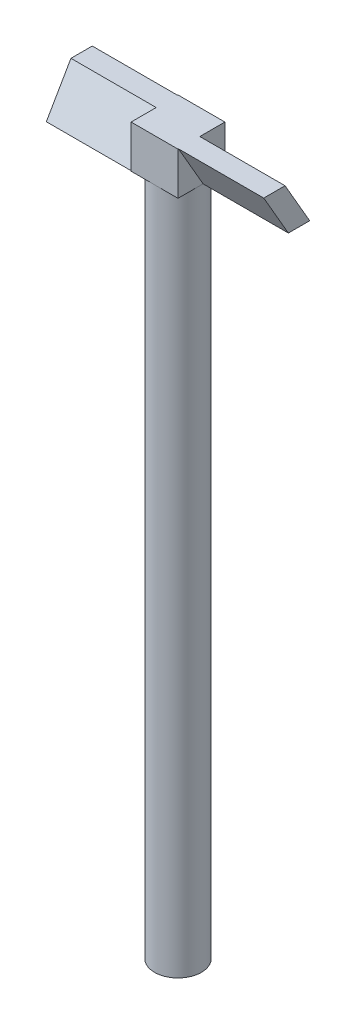
SolidWorks part; units mm, degrees
ref_plane "Front Plane" through (0, 0, 0) normal (0, 0, 1) x (1, 0, 0)
ref_plane "Top Plane" through (0, 0, 0) normal (0, 1, 0) x (1, 0, 0)
ref_plane "Right Plane" through (0, 0, 0) normal (1, 0, 0) x (0, 0, -1)
sketch "Sketch1" plane through (0, 0, 0) normal (0, 1, 0) x (1, 0, 0)
  circle A0 centre (0, 0) radius 5.5
  dimension "D1" = 11
extrude "Boss-Extrude1" add sketch "Sketch1" along normal blind 160 contours A0
sketch "Sketch2" plane through (0, 160, 0) normal (0, 1, 0) x (1, 0, 0)
  line L1 (-5.5, 5.5) -> (5.5, 5.5)
  line L2 (-5.5, 5.5) -> (-5.5, -5.5)
  line L3 (-5.5, -5.5) -> (5.5, -5.5)
  line L4 (5.5, 5.5) -> (5.5, -5.5)
  line L5 (-5.5, 5.5) -> (5.5, -5.5) construction
  line L6 (-5.5, -5.5) -> (5.5, 5.5) construction
  circle A0 centre (0, 0) radius 5.5 construction
  point P0 (0, 0)
  point P5 (0, -5.5)
  point P6 (0, 0)
extrude "Boss-Extrude2" add sketch "Sketch2" along normal blind 10
sketch "Sketch3" plane through (-5.5, 0, 0) normal (-1, 0, 0) x (0, 0, 1)
  line L0 (-5.3868, 170) -> (-0.3868, 170)
  line L1 (-5.5, 170) -> (5.5, 170) construction
  line L2 (-5.3868, 170) -> (0.3868, 160)
  line L3 (0, 160) -> (5.5, 160) construction
  line L4 (-0.3868, 170) -> (5.3868, 160)
  line L5 (5.3868, 160) -> (0.3868, 160)
  line L6 (-5.5, 160) -> (0, 160) construction
  line L7 (-2.8868, 170) -> (2.8868, 160) construction
  point P12 (0, 165)
  point P13 (0, 0)
  dimension "D1" = 60
  dimension "D2" = 5
extrude "Boss-Extrude3" add sketch "Sketch3" along normal blind 20
pattern_circular "CirPattern1" count 2 over 360 about axis through (0, 0, 0) along (0, 1, 0) of "Boss-Extrude3"
sketch "Sketch4" plane through (0, 0, 0) normal (0, -1, 0) x (1, 0, 0)
  circle A0 centre (0, 0) radius 1.625
  dimension "D1" = 3.25
extrude "Cut-Extrude1" cut sketch "Sketch4" against normal blind 45
